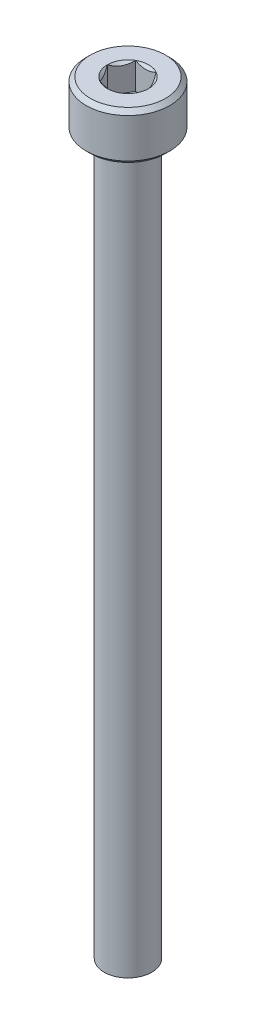
SolidWorks part; units mm, degrees
ref_plane "Front" through (0, 0, 0) normal (0, 0, 1) x (1, 0, 0)
ref_plane "Top" through (0, 0, 0) normal (0, 1, 0) x (1, 0, 0)
ref_plane "Right" through (0, 0, 0) normal (1, 0, 0) x (0, 0, -1)
sketch "Sketch1" plane through (0, 0, 0) normal (0, 1, 0) x (1, 0, 0)
  circle A0 centre (0, 0) radius 3.5
  dimension "D1" = 7
extrude "Boss-Extrude1" add sketch "Sketch1" along normal blind 4
sketch "Sketch2" plane through (0, 4, 0) normal (0, 1, 0) x (1, 0, 0)
  line L1 (0.866, 1.5) -> (-0.866, 1.5)
  line L2 (-0.866, 1.5) -> (-1.7321, 0)
  line L3 (-1.7321, 0) -> (-0.866, -1.5)
  line L4 (-0.866, -1.5) -> (0.866, -1.5)
  line L5 (0.866, -1.5) -> (1.7321, 0)
  line L6 (1.7321, 0) -> (0.866, 1.5)
  circle A0 centre (0, 0) radius 1.5 construction
  point P10 (0, 1.5)
  dimension "D1" = 3
extrude "Cut-Extrude1" cut sketch "Sketch2" against normal blind 2.25
sketch "Sketch3" plane through (0, 4, 0) normal (0, 1, 0) x (1, 0, 0)
  circle A0 centre (0, 0) radius 1.7321
extrude "Cut-Extrude2" cut sketch "Sketch3" against normal through all draft 45
chamfer "Chamfer1" distance 0.35 angle 45 2 edges at (0, 0, 3.5) (0, 4, 3.5)
sketch "草图1" plane through (0, 0, 0) normal (0, -1, 0) x (-1, 0, 0)
  circle A0 centre (0, 0) radius 2
  dimension "D1" = 4
extrude "凸台-拉伸1" add sketch "草图1" along normal blind 60
